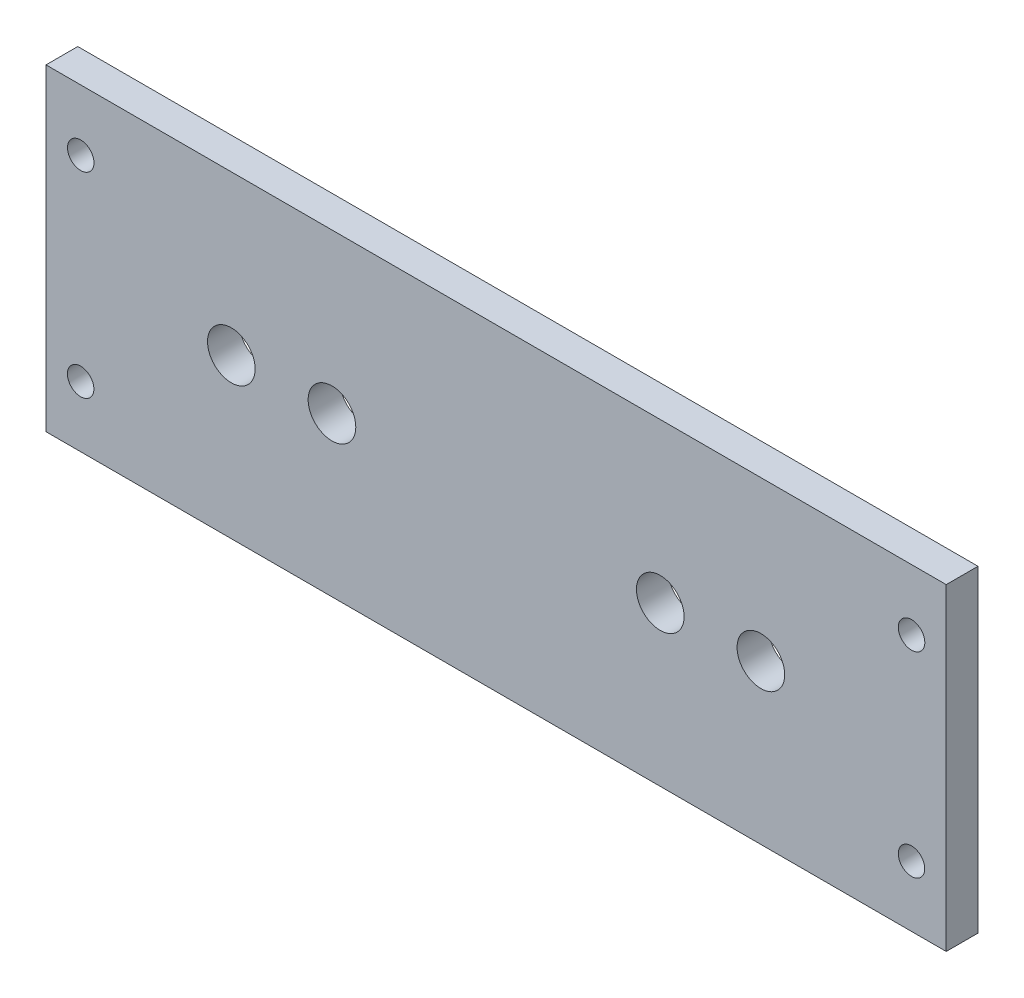
SolidWorks part; units mm, degrees
material "PE High Density"
ref_plane "Front Plane" through (0, 0, 0) normal (0, 0, 1) x (1, 0, 0)
ref_plane "Top Plane" through (0, 0, 0) normal (0, 1, 0) x (1, 0, 0)
ref_plane "Right Plane" through (0, 0, 0) normal (1, 0, 0) x (0, 0, -1)
ref_plane "Plane1" through (0, 0, 0) normal (0, 0, -1) x (-1, 0, 0)
sketch "Sketch1" plane through (0, 0, 0) normal (0, 0, -1) x (-1, 0, 0)
  line L0 (86, -25) -> (86, 35)
  line L1 (86, 35) -> (-84, 35)
  line L2 (-84, 35) -> (-84, -25)
  line L3 (-84, -25) -> (86, -25)
  circle A0 centre (-30, 5) radius 4.5
  circle A1 centre (-49, 5) radius 4.5
  circle A2 centre (32, 5) radius 4.5
  circle A3 centre (51, 5) radius 4.5
  circle A4 centre (79.445, 23.5) radius 2.5
  circle A5 centre (79.455, -13.5) radius 2.5
  circle A6 centre (-77.445, -13.5) radius 2.5
  circle A7 centre (-77.455, 23.5) radius 2.5
  dimension "D1" = 60
  dimension "D3" = 19
  dimension "D4" = 19
  dimension "D5" = 35
  dimension "D6" = 35
  dimension "D2" = 170
extrude "Boss-Extrude1" add sketch "Sketch1" against normal blind 6
